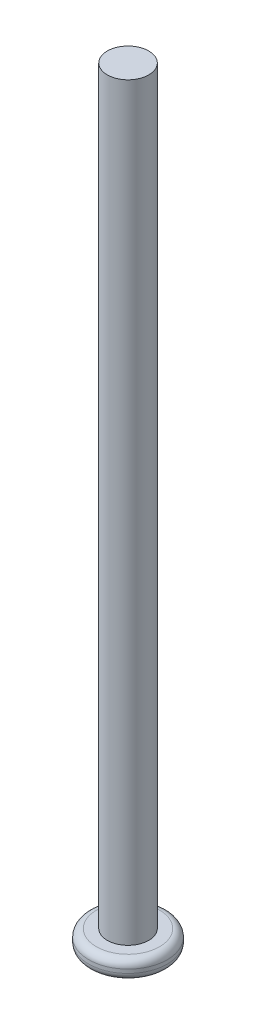
SolidWorks part; units mm, degrees
material "Plain Carbon Steel"
ref_plane "Front Plane" through (0, 0, 0) normal (0, 0, 1) x (1, 0, 0)
ref_plane "Top Plane" through (0, 0, 0) normal (0, 1, 0) x (1, 0, 0)
ref_plane "Right Plane" through (0, 0, 0) normal (1, 0, 0) x (0, 0, -1)
sketch "Sketch1" plane through (0, 0, 0) normal (0, 0, 1) x (1, 0, 0)
  line L0 (-2.75, 102) -> (-2.75, 2.5)
  line L1 (-2.75, 2.5) -> (-5.2, 2.5)
  line L2 (-5.2, 2.5) -> (-5.2, 0)
  line L3 (-5.2, 0) -> (0, 0)
  line L4 (0, 0) -> (0, 102) construction
  line L5 (-2.75, 102) -> (0, 102)
  line L6 (0, 0) -> (0, 102)
  dimension "D1" = 2.75
  dimension "D2" = 5.2
  dimension "D3" = 2.5
  dimension "D4" = 102
revolve "Revolve1" add sketch "Sketch1" angle 360 about L4
fillet "Fillet1" radius 1 2 edges at (5.2, 0, 0) (5.2, 2.5, 0)
